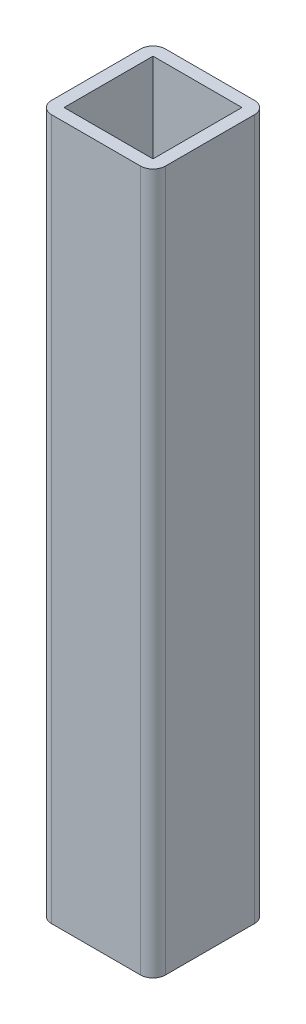
SolidWorks part; units mm, degrees
ref_plane "Front Plane" through (0, 0, 0) normal (0, 0, 1) x (1, 0, 0)
ref_plane "Top Plane" through (0, 0, 0) normal (0, 1, 0) x (1, 0, 0)
ref_plane "Right Plane" through (0, 0, 0) normal (1, 0, 0) x (0, 0, -1)
sketch "Sketch1" plane through (0, 0, 0) normal (0, 1, 0) x (1, 0, 0)
  line L1 (2.8, 0) -> (22.8, 0)
  line L2 (0, -2.8) -> (0, -22.8)
  line L3 (2.8, -25.6) -> (22.8, -25.6)
  line L4 (25.6, -2.8) -> (25.6, -22.8)
  arc A0 (22.8, 0) -> (25.6, -2.8) centre (22.8, -2.8) cw
  arc A1 (22.8, -25.6) -> (25.6, -22.8) centre (22.8, -22.8) ccw
  arc A2 (0, -22.8) -> (2.8, -25.6) centre (2.8, -22.8) ccw
  arc A3 (2.8, 0) -> (0, -2.8) centre (2.8, -2.8) ccw
  point P7 (25.6, 0)
  point P10 (25.6, -25.6)
  point P15 (0, 0)
  dimension "D2" = 2.8
  dimension "D1" = 25.6
extrude "Boss-Extrude1" add sketch "Sketch1" along normal blind 157.52
sketch "Sketch3" plane through (0, 0, 0) normal (0, -1, 0) x (-1, 0, 0)
  line L4 (-2.8, -2.8) -> (-22.8, -2.8)
  line L5 (-2.8, -2.8) -> (-2.8, -22.8)
  line L6 (-2.8, -22.8) -> (-22.8, -22.8)
  line L7 (-22.8, -2.8) -> (-22.8, -22.8)
  line L8 (-2.8, -2.8) -> (-22.8, -22.8) construction
  line L9 (-2.8, -22.8) -> (-22.8, -2.8) construction
  point P6 (-12.8, -12.8)
extrude "Cut-Extrude1" cut sketch "Sketch3" against normal blind 1040.5
